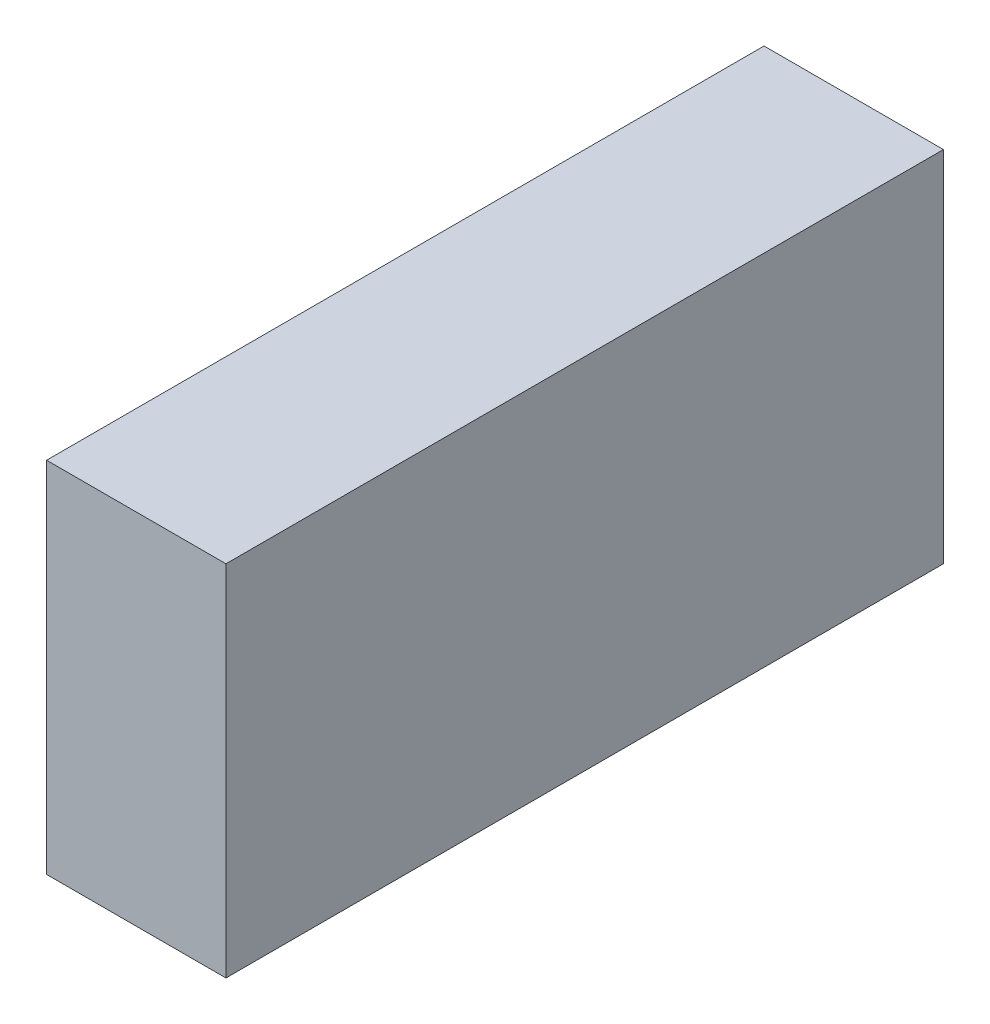
SolidWorks part; units mm, degrees
ref_plane "Front Plane" through (0, 0, 0) normal (0, 0, 1) x (1, 0, 0)
ref_plane "Top Plane" through (0, 0, 0) normal (0, 1, 0) x (1, 0, 0)
ref_plane "Right Plane" through (0, 0, 0) normal (1, 0, 0) x (0, 0, -1)
sketch "Sketch1" plane through (0, 0, 0) normal (1, 0, 0) x (0, 0, -1)
  line L1 (0, 0) -> (40, 0)
  line L2 (0, 0) -> (0, 20)
  line L3 (0, 20) -> (40, 20)
  line L4 (40, 0) -> (40, 20)
extrude "Boss-Extrude1" add sketch "Sketch1" against normal blind 10
